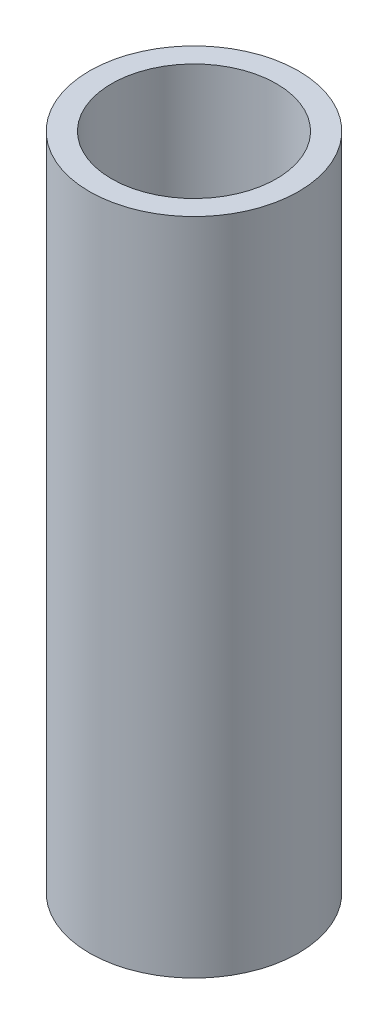
SolidWorks part; units mm, degrees
material "S-Glass Fiber"
ref_plane "Front Plane" through (0, 0, 0) normal (0, 0, 1) x (1, 0, 0)
ref_plane "Top Plane" through (0, 0, 0) normal (0, 1, 0) x (1, 0, 0)
ref_plane "Right Plane" through (0, 0, 0) normal (1, 0, 0) x (0, 0, -1)
sketch "Sketch1" plane through (0, 0, 0) normal (0, 0, 1) x (1, 0, 0)
  line L0 (0, 0) -> (0, -152.4) construction
  line L1 (-24.1554, 0) -> (-24.1554, -152.4)
  line L2 (-19.05, 0) -> (-19.05, -116.0015)
  line L3 (-19.05, -116.0015) -> (-6.35, -128.7015)
  line L4 (-6.35, -128.7015) -> (-12.7, -152.4)
  line L5 (-19.05, 0) -> (-24.1554, 0)
  line L6 (-12.7, -152.4) -> (-24.1554, -152.4)
  line L7 (-19.05, 0) -> (0, 0) construction
  dimension "D1" = 152.4
  dimension "D2" = 48.3108
  dimension "D3" = 38.1
  dimension "D4" = 12.7
  dimension "D5" = 25.4
  dimension "D6" = 45
  dimension "D7" = 15
revolve "body" add sketch "Sketch1" angle 360 about L0
